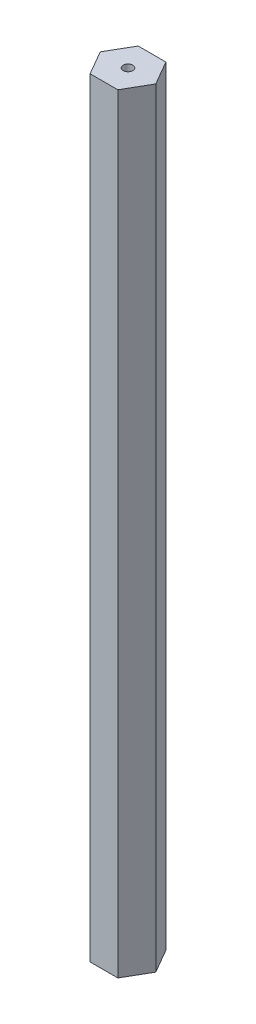
SolidWorks part; units mm, degrees
ref_plane "Front Plane" through (0, 0, 0) normal (0, 0, 1) x (1, 0, 0)
ref_plane "Top Plane" through (0, 0, 0) normal (0, 1, 0) x (1, 0, 0)
ref_plane "Right Plane" through (0, 0, 0) normal (1, 0, 0) x (0, 0, -1)
sketch "Sketch1" plane through (0, 0, 0) normal (0, 1, 0) x (1, 0, 0)
  line L1 (7.3323, 0) -> (3.6662, 6.35)
  line L2 (3.6662, 6.35) -> (-3.6662, 6.35)
  line L3 (-3.6662, 6.35) -> (-7.3323, 0)
  line L4 (-7.3323, 0) -> (-3.6662, -6.35)
  line L5 (-3.6662, -6.35) -> (3.6662, -6.35)
  line L6 (3.6662, -6.35) -> (7.3323, 0)
  circle A0 centre (0, 0) radius 6.35 construction
  circle A1 centre (0, 0) radius 1.27
  dimension "D2" = 2.54
  dimension "D1" = 12.7
extrude "Boss-Extrude1" add sketch "Sketch1" along normal blind 203.2
